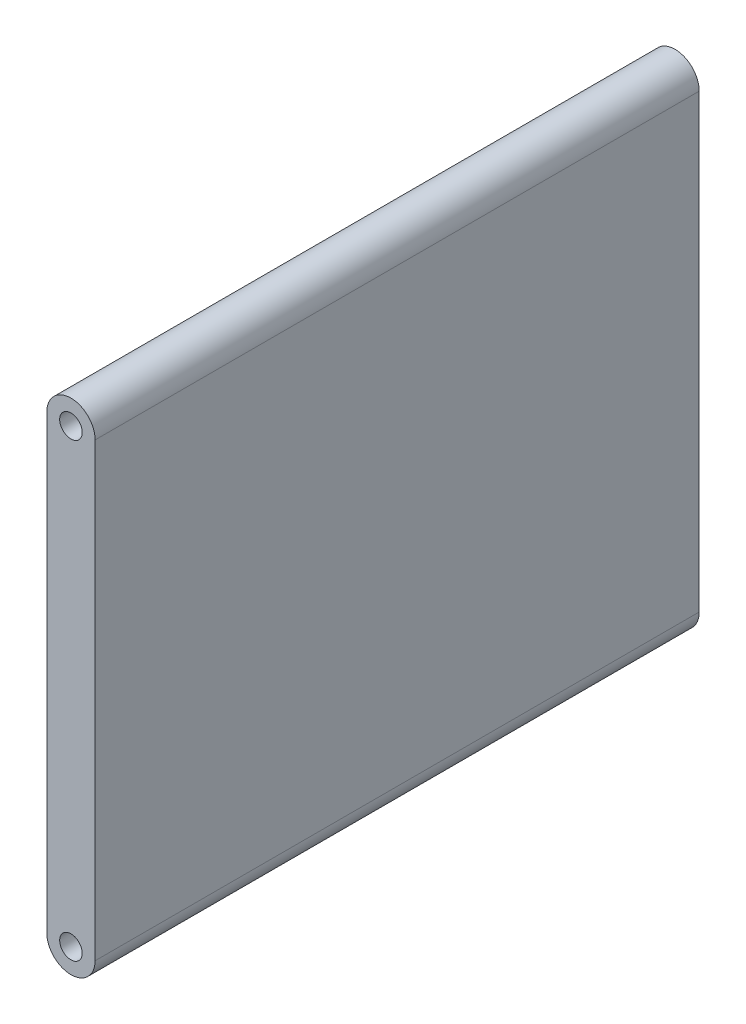
SolidWorks part; units mm, degrees
ref_plane "Alzado" through (0, 0, 0) normal (0, 0, 1) x (1, 0, 0)
ref_plane "Planta" through (0, 0, 0) normal (0, 1, 0) x (1, 0, 0)
ref_plane "Vista lateral" through (0, 0, 0) normal (1, 0, 0) x (0, 0, -1)
sketch "Croquis1" plane through (0, 0, 0) normal (0, 0, 1) x (1, 0, 0)
  line L0 (0, -28) -> (0, 28) construction
  line L1 (3, -28) -> (3, 28)
  line L2 (-3, -28) -> (-3, 28)
  circle A0 centre (0, 0) radius 32 construction
  arc A2 (3, -28) -> (-3, -28) centre (0, -28) cw
  arc A3 (3, 28) -> (-3, 28) centre (0, 28) ccw
  circle A4 centre (0, 28) radius 1.4
  circle A5 centre (0, -28) radius 1.4
  point P6 (0, 0)
  dimension "D1" = 64
  dimension "D5" = 2.8
  dimension "D2" = 56
  dimension "D3" = 3
  dimension "D4" = 3
extrude "Saliente-Extruir1" add sketch "Croquis1" along normal blind 75
